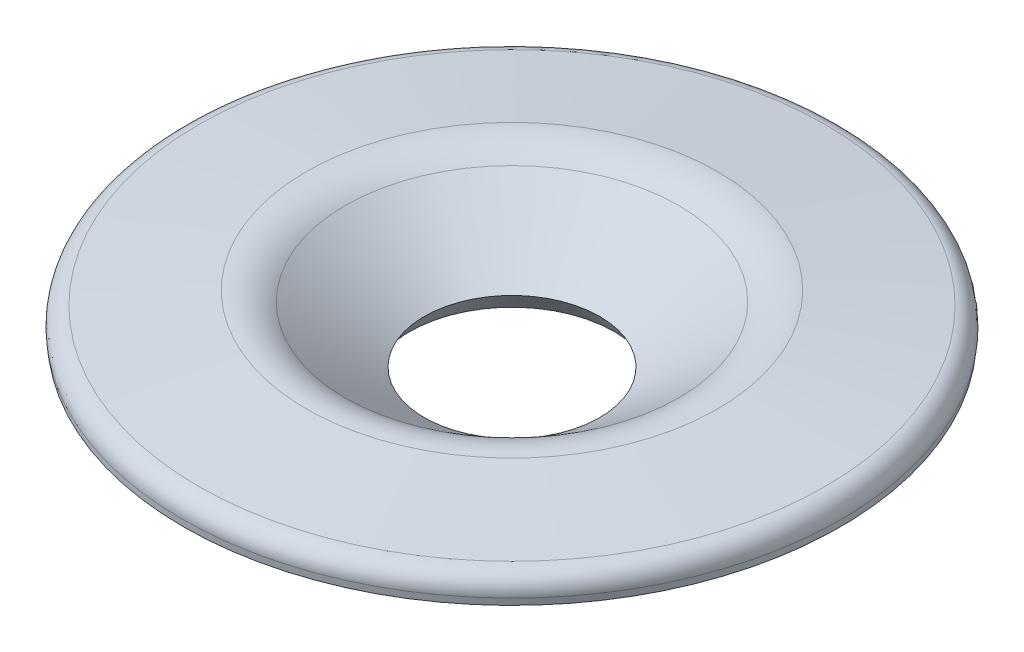
SolidWorks part; units mm, degrees
material "2024-T3"
ref_plane "Front Plane" through (0, 0, 0) normal (0, 0, 1) x (1, 0, 0)
ref_plane "Top Plane" through (0, 0, 0) normal (0, 1, 0) x (1, 0, 0)
ref_plane "Right Plane" through (0, 0, 0) normal (1, 0, 0) x (0, 0, -1)
sketch "Sketch1" plane through (0, 0, 0) normal (0, 0, 1) x (1, 0, 0)
  line L0 (0, 0) -> (0, 227.0636) construction
  line L1 (4.76, 0) -> (9.0495, 3.0698)
  line L2 (11.1602, 3.6079) -> (18, 2.77)
  arc A0 (9.0495, 3.0698) -> (11.1602, 3.6079) centre (10.7954, 0.6301) cw
  point P10 (10, 3.75)
  dimension "D6" = 3
  dimension "D1" = 9.52
  dimension "D2" = 20
  dimension "D3" = 36
  dimension "D4" = 3.75
  dimension "D5" = 0.98
revolve "Revolve-Thin2" add sketch "Sketch1" angle 360 about L0
fillet "Fillet1" radius 1 1 edges at (0, 2.77, -18)
